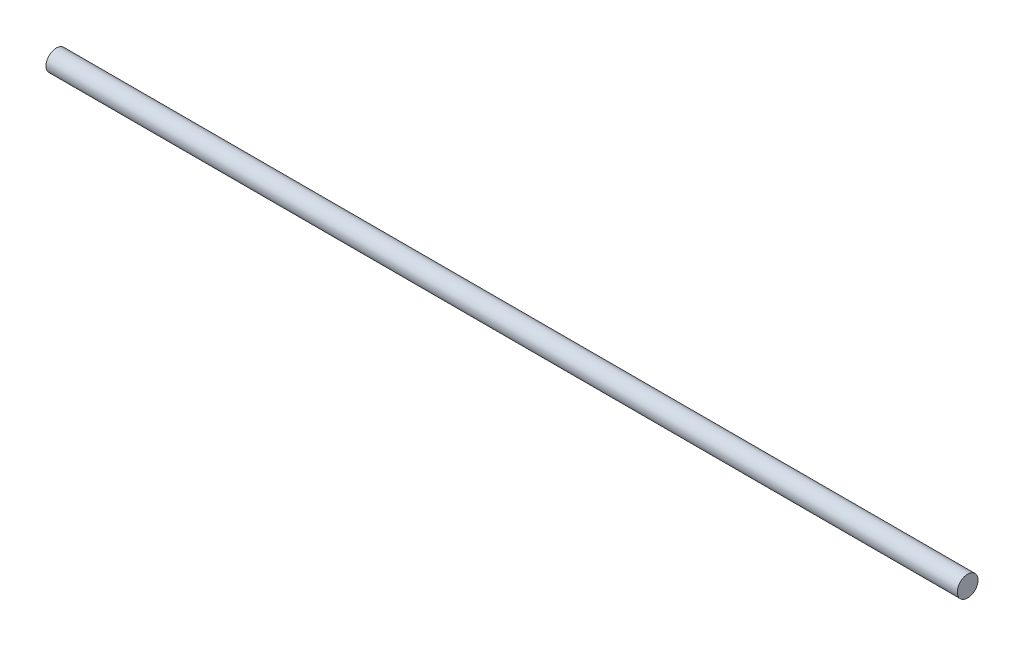
SolidWorks part; units mm, degrees
material "Thornel Mat VMA"
ref_plane "Front Plane" through (0, 0, 0) normal (0, 0, 1) x (1, 0, 0)
ref_plane "Top Plane" through (0, 0, 0) normal (0, 1, 0) x (1, 0, 0)
ref_plane "Right Plane" through (0, 0, 0) normal (1, 0, 0) x (0, 0, -1)
sketch "Sketch1" plane through (0, 0, 0) normal (0, 1, 0) x (1, 0, 0)
  line L1 (0, 0) -> (1117.6, 0)
  line L2 (0, 0) -> (0, 12.7)
  line L3 (0, 12.7) -> (1117.6, 12.7)
  line L4 (1117.6, 0) -> (1117.6, 12.7)
  point P9 (1193.5312, 55.9281)
  point P10 (1152.4144, 56.2679)
  point P11 (1154.7931, 68.8408)
  point P12 (1155.7084, 72.4845)
  point P13 (1161.5892, 51.8504)
  dimension "D1" = 1117.6
  dimension "D2" = 12.7
revolve "Revolve1" add sketch "Sketch1" angle 360 about L1
